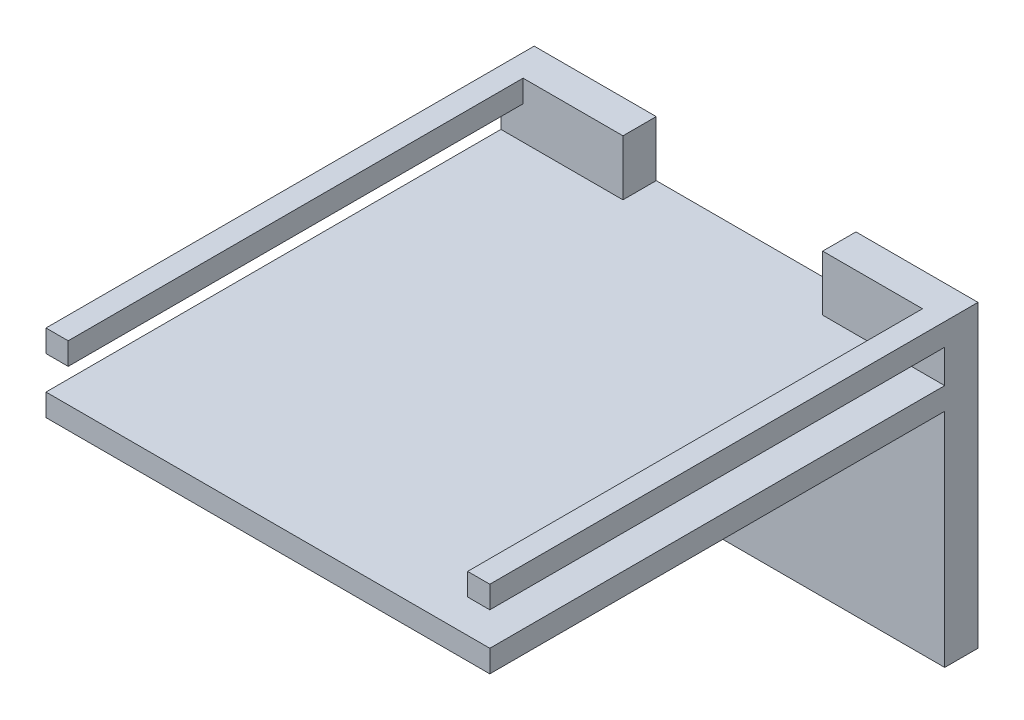
SolidWorks part; units mm, degrees
ref_plane "Plano frontal" through (0, 0, 0) normal (0, 0, 1) x (1, 0, 0)
ref_plane "Plano superior" through (0, 0, 0) normal (0, 1, 0) x (1, 0, 0)
ref_plane "Plano direito" through (0, 0, 0) normal (1, 0, 0) x (0, 0, -1)
sketch "Esboço1" plane through (0, 0, 0) normal (0, 0, 1) x (1, 0, 0)
  line L1 (7.1604, -0.5355) -> (27.1604, -0.5355)
  line L2 (7.1604, -0.5355) -> (7.1604, -4.0355)
  line L3 (7.1604, -4.0355) -> (27.1604, -4.0355)
  line L4 (27.1604, -0.5355) -> (27.1604, -4.0355)
  dimension "D1" = 20
  dimension "D2" = 3.5
extrude "Ressalto-extrusão1" add sketch "Esboço1" along normal blind 22
sketch "Esboço2" plane through (0, 0, 22) normal (0, 0, 1) x (1, 0, 0)
  line L0 (7.1604, -0.5355) -> (7.1604, -4.0355) construction
  line L1 (8.1604, 0.7654) -> (26.1604, 0.7654)
  line L2 (8.1604, 0.7654) -> (8.1604, -3.0355)
  line L3 (8.1604, -3.0355) -> (26.1604, -3.0355)
  line L4 (26.1604, 0.7654) -> (26.1604, -3.0355)
  line L5 (7.1604, -4.0355) -> (27.1604, -4.0355) construction
  line L6 (27.1604, -4.0355) -> (27.1604, -0.5355) construction
  dimension "D1" = 1
  dimension "D2" = 1
  dimension "D3" = 1
extrude "Corte-extrusão1" cut sketch "Esboço2" against normal blind 20.5
ref_plane "Plano1" through (0, -1.5355, 0) normal (0, 1, 0) x (1, 0, 0)
sketch "Esboço3" plane through (0, -1.5355, 0) normal (0, 1, 0) x (1, 0, 0)
  line L11 (8.1604, -1.5) -> (7.1604, -1.5)
  line L12 (8.1604, -1.5) -> (8.1604, -22)
  line L13 (8.1604, -22) -> (7.1604, -22)
  line L14 (7.1604, -1.5) -> (7.1604, -22)
  line L15 (26.1604, -1.5) -> (27.1604, -1.5)
  line L16 (26.1604, -1.5) -> (26.1604, -22)
  line L17 (26.1604, -22) -> (27.1604, -22)
  line L18 (27.1604, -1.5) -> (27.1604, -22)
extrude "Corte-extrusão2" cut sketch "Esboço3" against normal up to vertex (1.5 mm away)
sketch "Esboço4" plane through (0, -4.0355, 0) normal (0, -1, 0) x (1, 0, 0)
  line L0 (7.1604, 22) -> (7.1604, 0) construction
  line L1 (27.1604, 0) -> (7.1604, 0)
  line L2 (27.1604, 0) -> (27.1604, 1.5)
  line L3 (27.1604, 1.5) -> (7.1604, 1.5)
  line L4 (7.1604, 0) -> (7.1604, 1.5)
  dimension "D1" = 1.5
extrude "Ressalto-extrusão2" add sketch "Esboço4" along normal blind 10
sketch "Esboço5" plane through (0, 0, 1.5) normal (0, 0, 1) x (1, 0, 0)
  line L0 (7.1604, -9.0355) -> (27.1604, -9.0355) construction
  line L1 (7.1604, -14.0355) -> (7.1604, -4.0355) construction
  line L2 (27.1604, -14.0355) -> (27.1604, -4.0355) construction
  line L3 (17.1604, -14.0355) -> (17.1604, -4.0355) construction
  line L4 (27.1604, -14.0355) -> (7.1604, -14.0355) construction
  line L5 (7.1604, -4.0355) -> (27.1604, -4.0355) construction
  line L6 (17.1604, -4.0355) -> (7.1604, -14.0355) construction
  line L7 (7.1604, -4.0355) -> (17.1604, -14.0355) construction
  line L8 (17.1604, -4.0355) -> (27.1604, -14.0355) construction
  line L9 (17.1604, -14.0355) -> (27.1604, -4.0355) construction
  circle A0 centre (17.1604, -9.0355) radius 1.5
  point P19 (0, 0)
  dimension "D1" = 3
extrude "Corte-extrusão3" cut sketch "Esboço5" against normal blind 7
sketch "Esboço6" plane through (0, -0.5355, 0) normal (0, 1, 0) x (1, 0, 0)
  line L0 (17.1604, -1.5) -> (17.1604, 2.8719) construction
  line L1 (12.6604, 0.7752) -> (21.6604, 0.7752)
  line L2 (12.6604, 0.7752) -> (12.6604, -2.7433)
  line L3 (12.6604, -2.7433) -> (21.6604, -2.7433)
  line L4 (21.6604, 0.7752) -> (21.6604, -2.7433)
  line L5 (7.1604, -1.5) -> (27.1604, -1.5) construction
  dimension "D1" = 4.5
  dimension "D2" = 4.5
extrude "Corte-extrusão4" cut sketch "Esboço6" against normal up to surface (2.5 mm away) up to face at (17.1604, -3.0355, 11.75)
